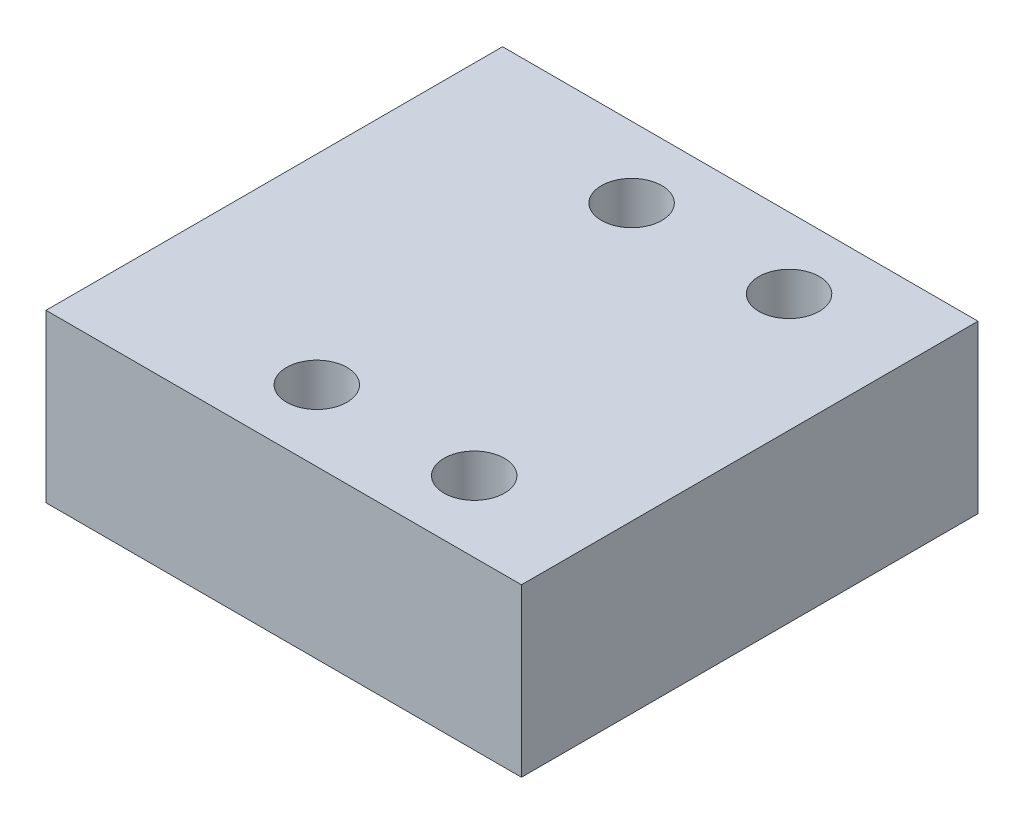
SolidWorks part; units mm, degrees
ref_plane "Front Plane" through (0, 0, 0) normal (0, 0, 1) x (1, 0, 0)
ref_plane "Top Plane" through (0, 0, 0) normal (0, 1, 0) x (1, 0, 0)
ref_plane "Right Plane" through (0, 0, 0) normal (1, 0, 0) x (0, 0, -1)
sketch "Sketch1" plane through (0, 0, 0) normal (0, 1, 0) x (1, 0, 0)
  line L0 (20.648, -2.6061) -> (-17.706, -2.6061) construction
  line L1 (-17.706, 15.8089) -> (20.648, 15.8089)
  line L2 (-17.706, 15.8089) -> (-17.706, -21.0211)
  line L3 (-17.706, -21.0211) -> (20.648, -21.0211)
  line L4 (20.648, 15.8089) -> (20.648, -21.0211)
  line L5 (4.773, 15.8089) -> (4.773, -21.0211) construction
  circle A0 centre (-1.577, 10.0939) radius 2.4384
  circle A1 centre (11.123, 10.0939) radius 2.4384
  circle A2 centre (11.123, -15.3061) radius 2.4384
  circle A3 centre (-1.577, -15.3061) radius 2.4384
  dimension "D4" = 4.8768
  dimension "D5" = 12.7
  dimension "D6" = 25.4
  dimension "D1" = 38.354
  dimension "D2" = 36.83
  dimension "D3" = 15.875
extrude "Boss-Extrude1" add sketch "Sketch1" along normal blind 13.4493
